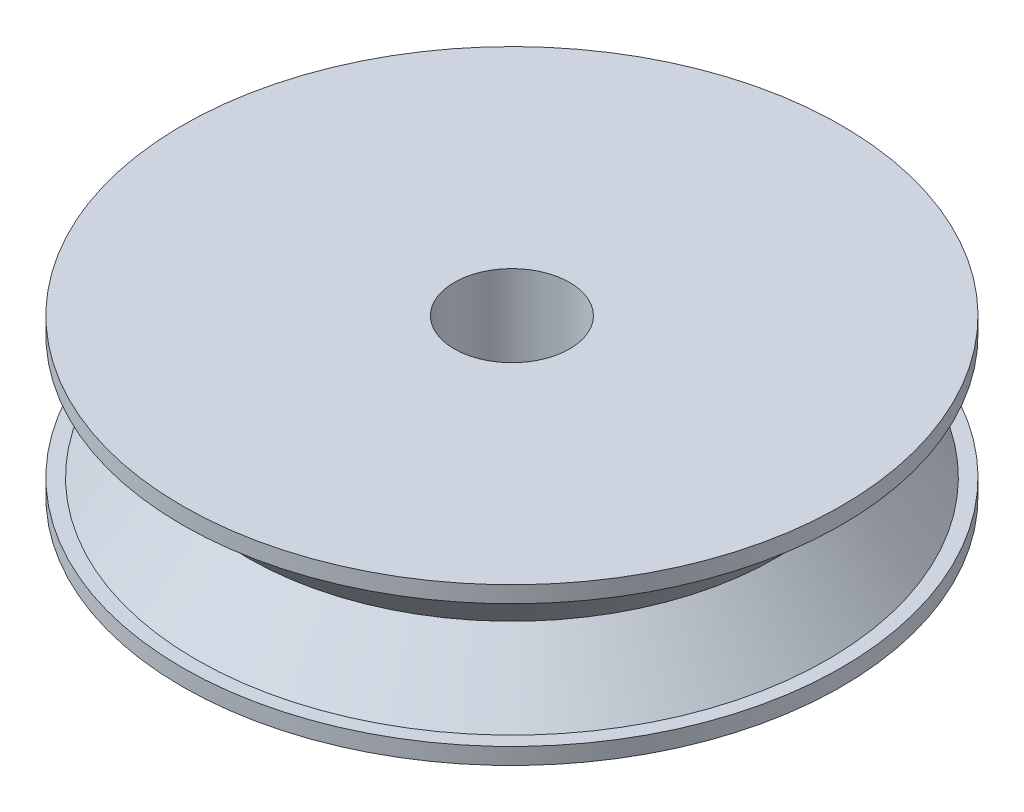
SolidWorks part; units mm, degrees
ref_plane "Front Plane" through (0, 0, 0) normal (0, 0, 1) x (1, 0, 0)
ref_plane "Top Plane" through (0, 0, 0) normal (0, 1, 0) x (1, 0, 0)
ref_plane "Right Plane" through (0, 0, 0) normal (1, 0, 0) x (0, 0, -1)
sketch "Sketch1" plane through (0, 0, 0) normal (0, 1, 0) x (1, 0, 0)
  circle A0 centre (0, 0) radius 10
  dimension "D1" = 20
extrude "Boss-Extrude1" add sketch "Sketch1" along normal blind 4.75
ref_axis "Axis1" through (0, 4.75, 0) along (0, -1, 0)
sketch "Sketch2" plane through (0, 0, 0) normal (1, 0, 0) x (0, 0, -1)
  line L0 (9.5789, 4.25) -> (8, 2.375)
  line L1 (8, 2.375) -> (9.5789, 0.5)
  line L2 (10, 0.5) -> (10, 4.25)
  line L3 (10, 2.375) -> (5.2537, 2.375) construction
  line L4 (10, 4.25) -> (9.5789, 4.25)
  line L5 (10, 4.75) -> (-10, 4.75) construction
  line L6 (10, 0.5) -> (9.5789, 0.5)
  dimension "D1" = 2
  dimension "D2" = 0.5
revolve "Cut-Revolve1" cut sketch "Sketch2" angle 360 about axis through (0, 4.75, 0) along (0, -1, 0)
sketch "Sketch3" plane through (0, 4.75, 0) normal (0, 1, 0) x (1, 0, 0)
  circle A0 centre (0, 0) radius 1.75
  dimension "D1" = 3.5
extrude "Cut-Extrude1" cut sketch "Sketch3" against normal blind 4.75
